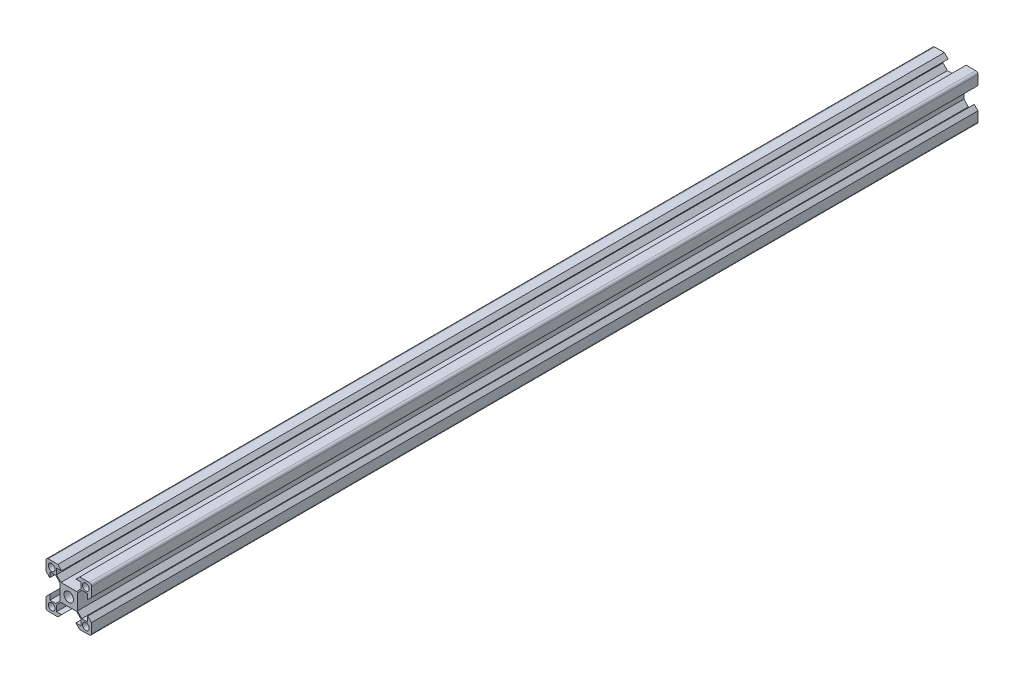
SolidWorks part; units mm, degrees
material "铝管"
ref_plane "前视基准面" through (0, 0, 0) normal (0, 0, 1) x (1, 0, 0)
ref_plane "上视基准面" through (0, 0, 0) normal (0, 1, 0) x (1, 0, 0)
ref_plane "右视基准面" through (0, 0, 0) normal (1, 0, 0) x (0, 0, -1)
sketch "草图1" plane through (0, 0, 0) normal (0, 0, 1) x (1, 0, 0)
  line L0 (0, 0) -> (-40.5659, 40.5659) construction
  line L1 (0, 0) -> (0, 75.5033) construction
  line L2 (-10, 10) -> (-10, 4.8)
  line L3 (-10, 4.8) -> (-8.34, 3.14)
  line L4 (-8.34, 3.14) -> (-8.34, 5.4)
  line L5 (-5.7536, 5.4) -> (-3.8, 3.4464)
  line L6 (-3.8, 3.4464) -> (-3.8, -3.4464)
  line L7 (-3.8, 0) -> (15.6715, 0) construction
  line L8 (-5.4, 8.34) -> (-5.4, 5.7536)
  line L9 (-3.4464, 3.8) -> (3.4464, 3.8)
  line L10 (-5.4, 5.7536) -> (-3.4464, 3.8)
  line L11 (-3.14, 8.34) -> (-5.4, 8.34)
  line L12 (-8.34, 5.4) -> (-5.7536, 5.4)
  line L13 (-4.8, 10) -> (-3.14, 8.34)
  line L14 (-10, 10) -> (-4.8, 10)
  line L15 (-10, -10) -> (-4.8, -10)
  line L16 (-4.8, -10) -> (-3.14, -8.34)
  line L17 (-8.34, -5.4) -> (-5.7536, -5.4)
  line L18 (-3.14, -8.34) -> (-5.4, -8.34)
  line L19 (-5.4, -5.7536) -> (-3.4464, -3.8)
  line L20 (-3.4464, -3.8) -> (3.4464, -3.8)
  line L21 (-5.4, -8.34) -> (-5.4, -5.7536)
  line L22 (-5.7536, -5.4) -> (-3.8, -3.4464)
  line L23 (-8.34, -3.14) -> (-8.34, -5.4)
  line L24 (-10, -4.8) -> (-8.34, -3.14)
  line L25 (-10, -10) -> (-10, -4.8)
  line L26 (10, -10) -> (10, -4.8)
  line L27 (10, -4.8) -> (8.34, -3.14)
  line L28 (8.34, -3.14) -> (8.34, -5.4)
  line L29 (5.7536, -5.4) -> (3.8, -3.4464)
  line L30 (5.4, -8.34) -> (5.4, -5.7536)
  line L31 (5.4, -5.7536) -> (3.4464, -3.8)
  line L32 (3.14, -8.34) -> (5.4, -8.34)
  line L33 (8.34, -5.4) -> (5.7536, -5.4)
  line L34 (4.8, -10) -> (3.14, -8.34)
  line L35 (10, -10) -> (4.8, -10)
  line L36 (10, 10) -> (4.8, 10)
  line L37 (4.8, 10) -> (3.14, 8.34)
  line L38 (8.34, 5.4) -> (5.7536, 5.4)
  line L39 (3.14, 8.34) -> (5.4, 8.34)
  line L40 (5.4, 5.7536) -> (3.4464, 3.8)
  line L41 (5.4, 8.34) -> (5.4, 5.7536)
  line L42 (3.8, 3.4464) -> (3.8, -3.4464)
  line L43 (5.7536, 5.4) -> (3.8, 3.4464)
  line L44 (8.34, 3.14) -> (8.34, 5.4)
  line L45 (10, 4.8) -> (8.34, 3.14)
  line L46 (10, 10) -> (10, 4.8)
  circle A0 centre (-7.5, 7.5) radius 1.5
  circle A1 centre (0, 0) radius 2.1
  circle A2 centre (-7.5, -7.5) radius 1.5
  circle A3 centre (7.5, -7.5) radius 1.5
  circle A4 centre (7.5, 7.5) radius 1.5
  point P54 (0, -3.8)
  point P64 (0, 3.8)
  dimension "D6" = 3
  dimension "D7" = 7.5
  dimension "D9" = 4.2
  dimension "D1" = 45
  dimension "D2" = 4.8
  dimension "D3" = 3.8
  dimension "D4" = 10
  dimension "D5" = 5.4
  dimension "D8" = 3.14
  dimension "D10" = 10
  dimension "D11" = 0.5
extrude "凸台-拉伸1" add sketch "草图1" along normal mid plane 390
fillet "圆角1" radius 1 4 edges at (-10, -10, 0) (10, -10, 0) (-10, 10, 0) (10, 10, 0)
